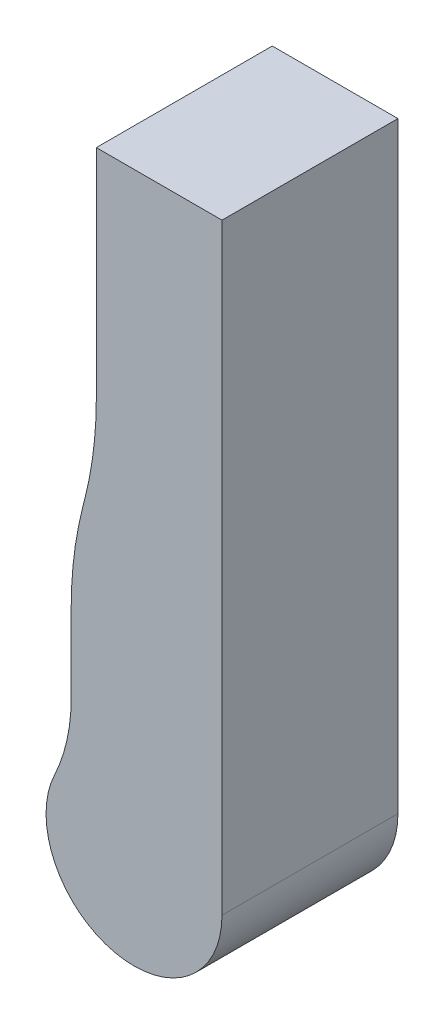
SolidWorks part; units mm, degrees
ref_plane "Plan de face" through (0, 0, 0) normal (0, 0, 1) x (1, 0, 0)
ref_plane "Plan de dessus" through (0, 0, 0) normal (0, 1, 0) x (1, 0, 0)
ref_plane "Plan de droite" through (0, 0, 0) normal (1, 0, 0) x (0, 0, -1)
sketch "Esquisse1" plane through (0, 0, 0) normal (0, 0, 1) x (1, 0, 0)
  line L2 (-5, 0) -> (-5, -10.5)
  line L5 (-5, 0) -> (0, 0)
  line L10 (-6, -14.5) -> (-6, -21.5)
  line L13 (-6, -14.5) -> (-5, -10.5)
  line L14 (-3.5, -23.9495) -> (0, -23.9495) construction
  line L15 (0, 0) -> (0, -23.9495)
  arc A1 (-6, -21.5) -> (0, -23.9495) centre (-3.5, -23.9495) ccw
  point P0 (0, 0)
  point P1 (0, 0)
  point P5 (0, 0)
  point P7 (0, 0)
  point P9 (0, 0)
  dimension "D5" = 7
  dimension "D1" = 5
  dimension "D2" = 10.5
  dimension "D3" = 4
  dimension "D4" = 1
  dimension "D6" = 7
  dimension "D8" = 3.5
  dimension "D9" = 3.5
extrude "Boss.-Extru.2" add sketch "Esquisse1" along normal blind 7 contours L13 L2 L5 L15 A1 L10
fillet "Congé1" radius 7 1 edges at (-6, -21.5, 3.5)
fillet "Congé2" radius 15 2 edges at (-6, -14.5, 3.5) (-5, -10.5, 3.5)
